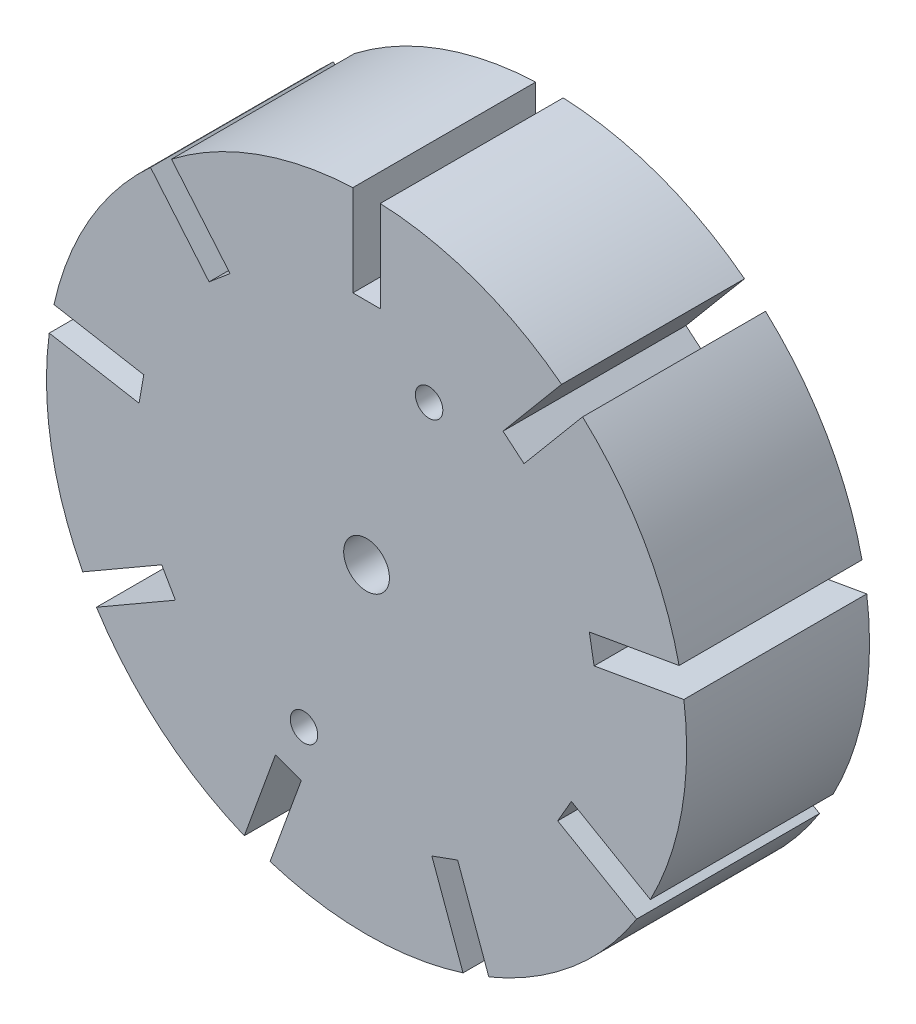
SolidWorks part; units mm, degrees
ref_plane "前视基准面" through (0, 0, 0) normal (0, 0, 1) x (1, 0, 0)
ref_plane "上视基准面" through (0, 0, 0) normal (0, 1, 0) x (1, 0, 0)
ref_plane "右视基准面" through (0, 0, 0) normal (1, 0, 0) x (0, 0, -1)
sketch "草图1" plane through (0, 0, 0) normal (0, 0, 1) x (1, 0, 0)
  circle A0 centre (0, 0) radius 35
  circle A1 centre (0, 0) radius 2.5
  dimension "D1" = 70
  dimension "D2" = 5
extrude "凸台-拉伸1" add sketch "草图1" along normal blind 20
sketch "草图2" plane through (0, 0, 20) normal (0, 0, 1) x (1, 0, 0)
  line L0 (0, 0) -> (0, 35) construction
  line L1 (-1.5, 25) -> (1.5, 25) construction
  line L2 (-1.5, 25) -> (1.5, 25)
  line L3 (-1.5, 25) -> (-1.5, 34.9678)
  line L4 (1.5, 25) -> (1.5, 34.9678)
  circle A0 centre (0, 0) radius 35 construction
  arc A1 (1.5, 34.9678) -> (-1.5, 34.9678) centre (0, 0) ccw
  point P9 (0, 25)
  point P11 (0, 25)
  dimension "D1" = 3
  dimension "D2" = 10
extrude "切除-拉伸1" cut sketch "草图2" against normal up to surface (20 mm away) up to face at (35, 0, 0)
pattern_circular "阵列(圆周)1" count 9 over 360 about axis through (0, 0, 0) along (0, 0, 1) of "切除-拉伸1"
sketch "草图3" plane through (0, 0, 20) normal (0, 0, 1) x (1, 0, 0)
  line L0 (0, 25) -> (0, 0) construction
  line L1 (-1.5, 25) -> (1.5, 25) construction
  line L2 (0, 0) -> (6.8404, 18.7939) construction
  line L3 (0, 0) -> (-6.8404, -18.7939) construction
  circle A0 centre (6.8404, 18.7939) radius 1.5
  circle A1 centre (-6.8404, -18.7939) radius 1.5
  dimension "D3" = 3
  dimension "D5" = 3
  dimension "D1" = 20
  dimension "D2" = 20
  dimension "D4" = 20
extrude "切除-拉伸2" cut sketch "草图3" against normal up to surface (20 mm away) up to face at (0, 0, 0)
